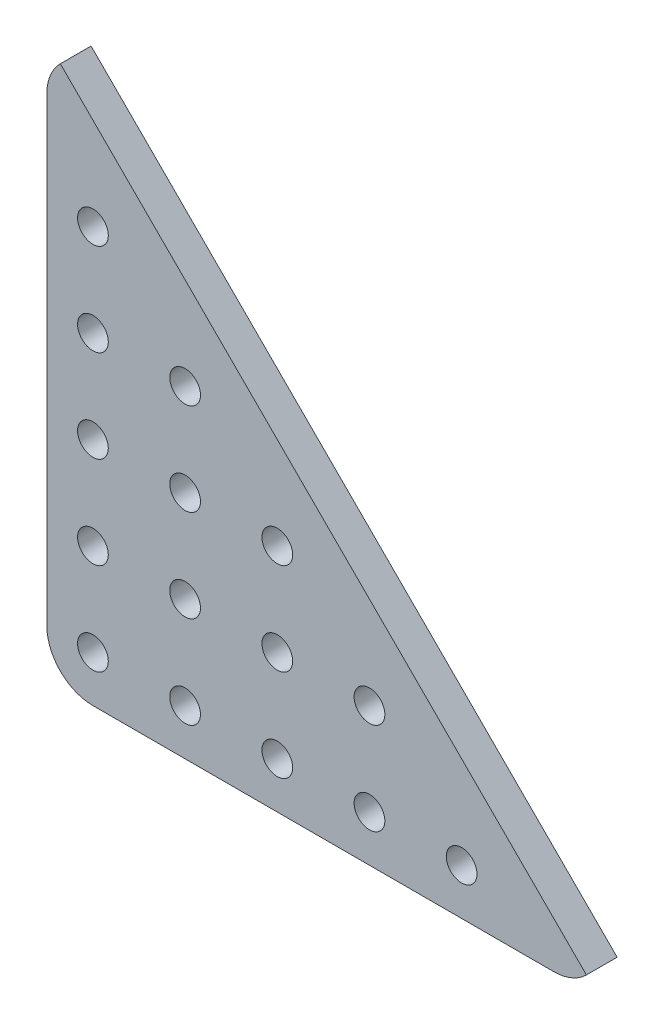
SolidWorks part; units mm, degrees
ref_plane "Alzado" through (0, 0, 0) normal (0, 0, 1) x (1, 0, 0)
ref_plane "Planta" through (0, 0, 0) normal (0, 1, 0) x (1, 0, 0)
ref_plane "Vista lateral" through (0, 0, 0) normal (1, 0, 0) x (0, 0, -1)
sketch "Model" plane through (0, 0, 0) normal (0, 0, 1) x (1, 0, 0)
  line L0 (-105.9434, 101.0565) -> (-105.9434, 56.0565)
  line L1 (-101.4434, 51.5565) -> (-56.4434, 51.5565)
  line L2 (-104.6254, 104.2385) -> (-53.2614, 52.8746)
  circle A0 centre (-101.4434, 92.0565) radius 1.5
  circle A1 centre (-101.4434, 83.0565) radius 1.5
  circle A2 centre (-92.4434, 83.0565) radius 1.5
  arc A3 (-104.6254, 104.2385) -> (-105.9434, 101.0565) centre (-101.4434, 101.0565) ccw
  arc A4 (-105.9434, 56.0565) -> (-101.4434, 51.5565) centre (-101.4434, 56.0565) ccw
  arc A5 (-56.4434, 51.5565) -> (-53.2614, 52.8746) centre (-56.4434, 56.0565) ccw
  circle A6 centre (-101.4434, 74.0565) radius 1.5
  circle A7 centre (-92.4434, 74.0565) radius 1.5
  circle A8 centre (-83.4434, 74.0565) radius 1.5
  circle A9 centre (-101.4434, 65.0565) radius 1.5
  circle A10 centre (-92.4434, 65.0565) radius 1.5
  circle A11 centre (-83.4434, 65.0565) radius 1.5
  circle A12 centre (-74.4434, 65.0565) radius 1.5
  circle A13 centre (-101.4434, 56.0565) radius 1.5
  circle A14 centre (-92.4434, 56.0565) radius 1.5
  circle A15 centre (-83.4434, 56.0565) radius 1.5
  circle A16 centre (-74.4434, 56.0565) radius 1.5
  circle A17 centre (-65.4434, 56.0565) radius 1.5
extrude "Saliente-Extruir1" add sketch "Model" along normal blind 3
